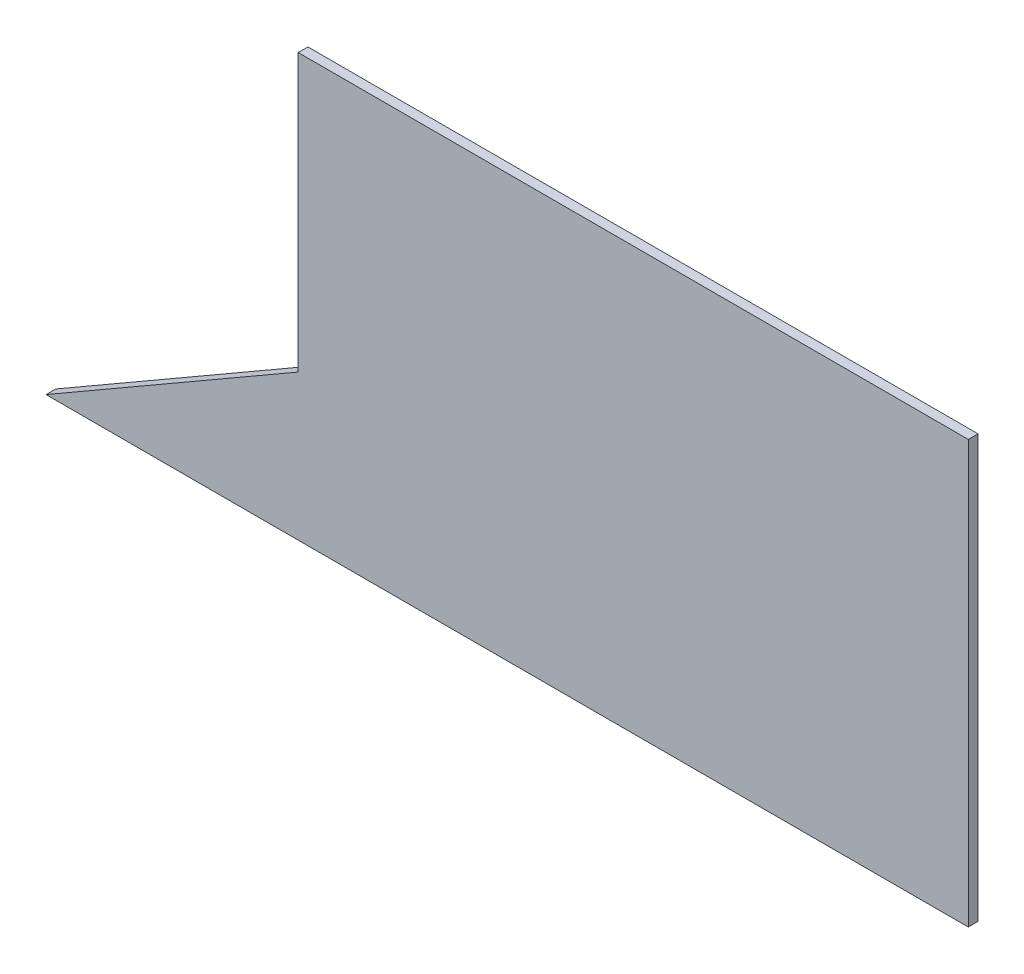
SolidWorks part; units mm, degrees
material "Acrylic (Medium-high impact)"
ref_plane "Front Plane" through (0, 0, 0) normal (0, 0, 1) x (1, 0, 0)
ref_plane "Top Plane" through (0, 0, 0) normal (0, 1, 0) x (1, 0, 0)
ref_plane "Right Plane" through (0, 0, 0) normal (1, 0, 0) x (0, 0, -1)
sketch "Sketch1" plane through (0, 0, 0) normal (0, 0, 1) x (1, 0, 0)
  line L0 (-82.6429, -41.631) -> (107.3571, -41.631)
  line L1 (107.3571, -41.631) -> (107.3571, 45.369)
  line L2 (107.3571, 45.369) -> (-30.6813, 45.369)
  line L3 (-30.6813, 45.369) -> (-30.6813, -11.631)
  line L4 (-30.6813, -11.631) -> (-82.6429, -41.631)
  dimension "D1" = 190
  dimension "D2" = 87
  dimension "D3" = 60
  dimension "D4" = 30
  dimension "D5" = 57
extrude "Boss-Extrude1" add sketch "Sketch1" along normal blind 2
